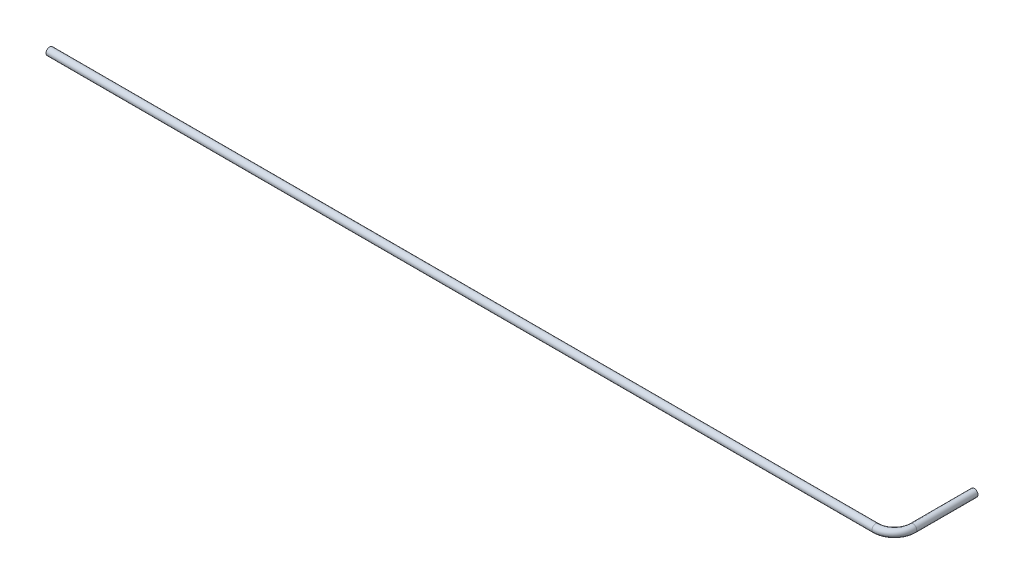
SolidWorks part; units mm, degrees
ref_plane "Front Plane" through (0, 0, 0) normal (0, 0, 1) x (1, 0, 0)
ref_plane "Top Plane" through (0, 0, 0) normal (0, 1, 0) x (1, 0, 0)
ref_plane "Right Plane" through (0, 0, 0) normal (1, 0, 0) x (0, 0, -1)
sketch "Sketch1" plane through (0, 0, 0) normal (0, 1, 0) x (1, 0, 0)
  line L0 (0, 10.8576) -> (0, 2.54)
  line L1 (-2.54, 0) -> (-114.7426, 0)
  arc A0 (0, 2.54) -> (-2.54, 0) centre (-2.54, 2.54) cw
  point P6 (0, 0)
ref_plane "Plane1" through (0, 0, -10.8576) normal (0, 0, 1) x (1, 0, 0)
sketch "Sketch3" plane through (0, 0, -10.8576) normal (0, 0, 1) x (1, 0, 0)
  circle A0 centre (0, 0) radius 0.5
  dimension "D1" = 1
sweep "Sweep1" add profiles "Sketch3" path "Sketch1"
